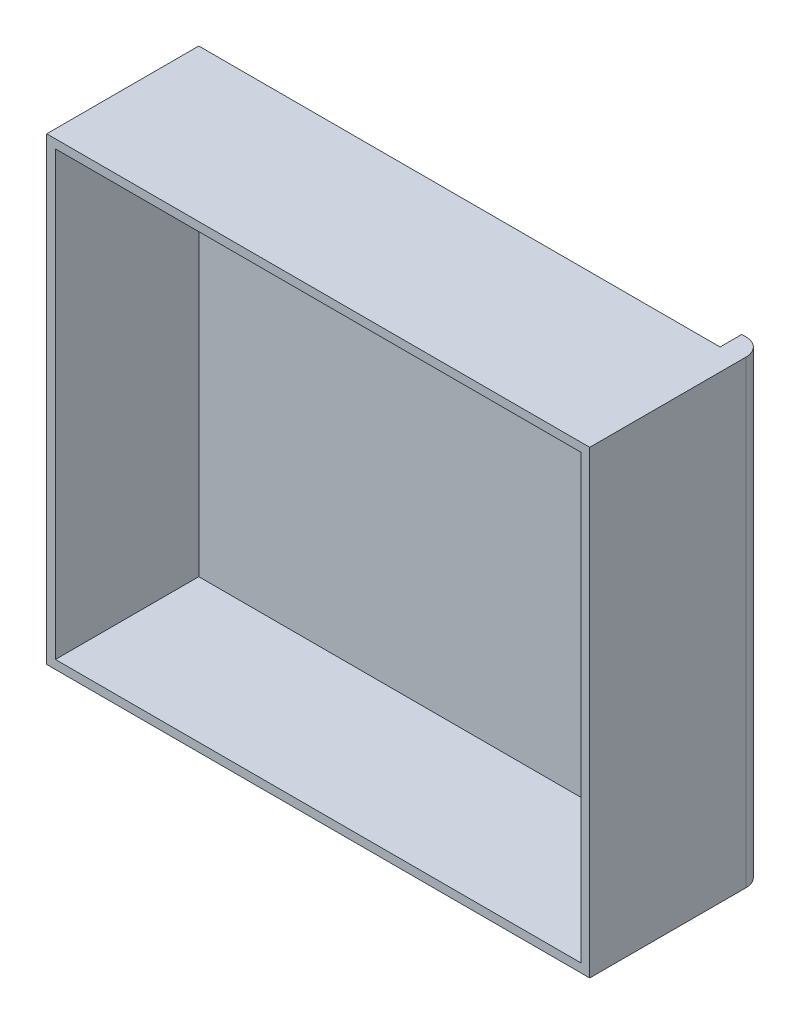
SolidWorks part; units mm, degrees
ref_plane "前视基准面" through (0, 0, 0) normal (0, 0, 1) x (1, 0, 0)
ref_plane "上视基准面" through (0, 0, 0) normal (0, 1, 0) x (1, 0, 0)
ref_plane "右视基准面" through (0, 0, 0) normal (1, 0, 0) x (0, 0, -1)
sketch "草图1" plane through (0, 0, 0) normal (0, 0, 1) x (1, 0, 0)
  line L1 (0, 0) -> (125, 0)
  line L2 (0, 0) -> (0, 105.8)
  line L3 (0, 105.8) -> (125, 105.8)
  line L4 (125, 0) -> (125, 105.8)
  dimension "D1" = 105.8
  dimension "D2" = 125
extrude "凸台-拉伸1" add sketch "草图1" along normal blind 35
shell "抽壳1" thickness 2
sketch "草图2" plane through (0, 0, 0) normal (0, 0, -1) x (-1, 0, 0)
  line L0 (0, 0) -> (-125, 0) construction
  line L1 (-125, 105.8) -> (-120, 105.8)
  line L2 (-125, 105.8) -> (-125, 0)
  line L3 (-125, 0) -> (-120, 0)
  line L4 (-120, 105.8) -> (-120, 0)
  dimension "D1" = 5
extrude "凸台-拉伸2" add sketch "草图2" along normal blind 5
fillet "圆角1" radius 4 1 edges at (125, 52.9, -5)
